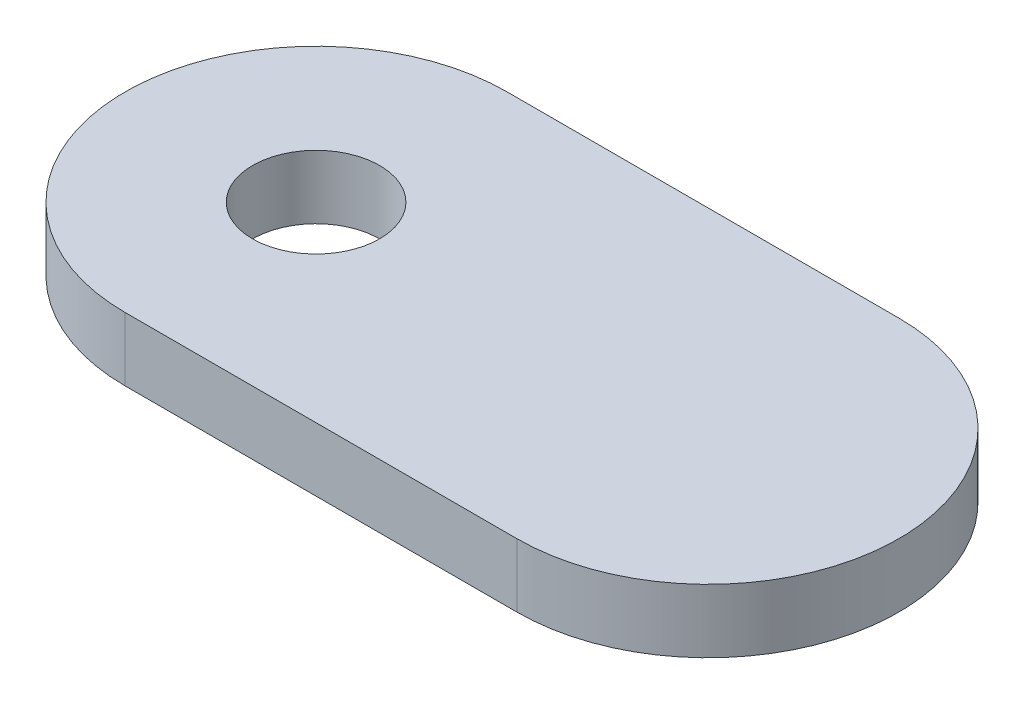
SolidWorks part; units mm, degrees
material "ABS"
ref_plane "Płaszczyzna przednia" through (0, 0, 0) normal (0, 0, 1) x (1, 0, 0)
ref_plane "Płaszczyzna górna" through (0, 0, 0) normal (0, 1, 0) x (1, 0, 0)
ref_plane "Płaszczyzna prawa" through (0, 0, 0) normal (1, 0, 0) x (0, 0, -1)
sketch "Szkic1" plane through (0, 0, 0) normal (0, 1, 0) x (1, 0, 0)
  line L0 (0, 0) -> (61.6043, 0) construction
  line L1 (0, 30.0321) -> (61.6043, 30.0321)
  line L2 (0, -30.0321) -> (61.6043, -30.0321)
  arc A0 (0, 30.0321) -> (0, -30.0321) centre (0, 0) ccw
  arc A1 (61.6043, -30.0321) -> (61.6043, 30.0321) centre (61.6043, 0) ccw
  point P3 (30.8021, 0)
extrude "Dodanie-wyciągnięcie1" add sketch "Szkic1" along normal blind 10
sketch "Szkic2" plane through (0, 10, 0) normal (0, 1, 0) x (1, 0, 0)
  circle A0 centre (0, 0) radius 9.9931
extrude "Wytnij-wyciągnięcie1" cut sketch "Szkic2" against normal up to next
